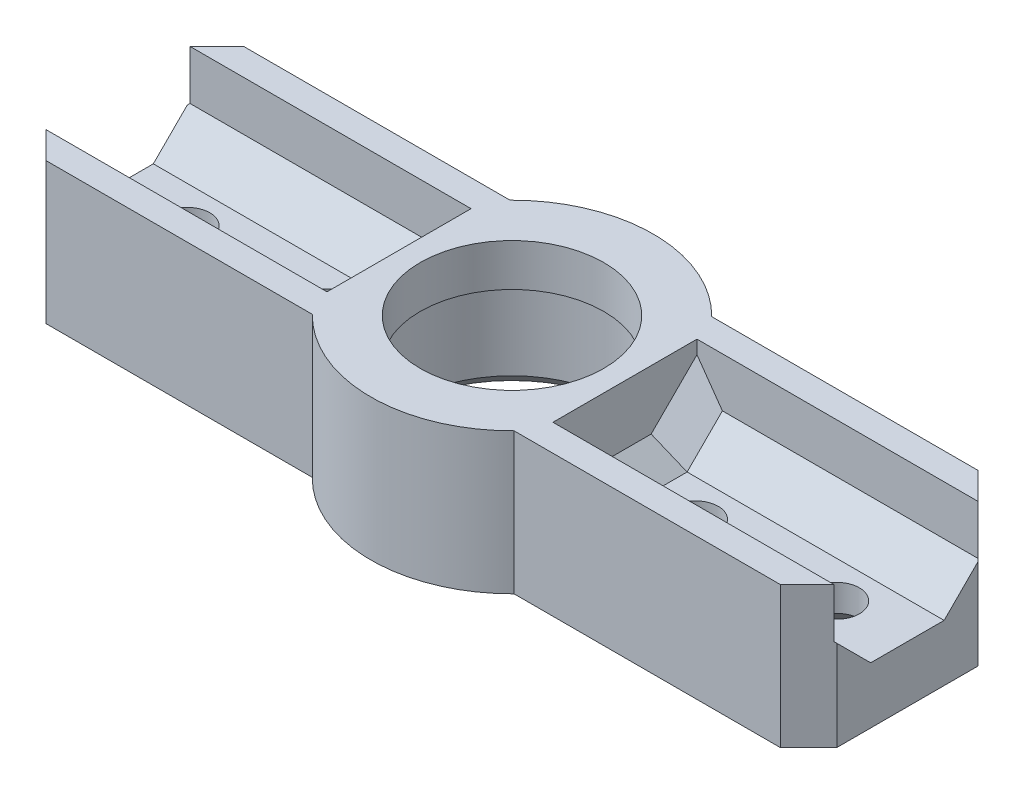
SolidWorks part; units mm, degrees
ref_plane "Plan de face" through (0, 0, 0) normal (0, 0, 1) x (1, 0, 0)
ref_plane "Plan de dessus" through (0, 0, 0) normal (0, 1, 0) x (1, 0, 0)
ref_plane "Plan de droite" through (0, 0, 0) normal (1, 0, 0) x (0, 0, -1)
sketch "Esquisse1" plane through (0, 0, 0) normal (0, 1, 0) x (1, 0, 0)
  line L0 (7.1414, 7) -> (28, 7)
  line L1 (-28, -7) -> (-7.1414, -7)
  line L2 (-28, -7) -> (-28, 7)
  line L3 (-28, 7) -> (-7.1414, 7)
  line L4 (28, -7) -> (28, 7)
  line L5 (-28, -7) -> (28, 7) construction
  line L6 (-28, 7) -> (28, -7) construction
  line L7 (7.1414, -7) -> (28, -7)
  arc A0 (-7.1414, -7) -> (7.1414, -7) centre (0, 0) ccw
  arc A1 (7.1414, 7) -> (-7.1414, 7) centre (0, 0) ccw
  dimension "D1" = 20
  dimension "D2" = 14
  dimension "D3" = 56
extrude "Boss.-Extru.1" add sketch "Esquisse1" along normal blind 10
sketch "Esquisse2" plane through (-28, 0, 0) normal (-1, 0, 0) x (0, 0, 1)
  line L0 (-7, 10) -> (7, 10) construction
  line L1 (-5.1, 10) -> (5.1, 10)
  line L2 (-5.1, 10) -> (-5.1, 4)
  line L3 (-5.1, 4) -> (5.1, 4)
  line L4 (5.1, 10) -> (5.1, 4)
  line L5 (-7, 0) -> (7, 0) construction
  point P6 (0, 0)
  dimension "D1" = 6
  dimension "D2" = 10.2
  dimension "D3" = 5.1
extrude "Enlèv. mat.-Extru.1" cut sketch "Esquisse2" against normal blind 20
chamfer "Chanfrein1" distance 2.5 angle 45 2 edges at (-18, 4, 5.1) (-18, 4, -5.1)
chamfer "Chanfrein2" distance 1.8 angle 45 3 edges at (-8, 5.25, 3.85) (-8, 4, 0) (-8, 5.25, -3.85)
mirror "Symétrie1" about plane through (0, 0, 0) normal (1, 0, 0) of "Chanfrein2", "Chanfrein1", "Enlèv. mat.-Extru.1"
sketch "Esquisse3" plane through (0, 0, 0) normal (0, -1, 0) x (1, 0, 0)
  circle A0 centre (0, 0) radius 6.5
  dimension "D1" = 13
extrude "Enlèv. mat.-Extru.2" cut sketch "Esquisse3" against normal through all
sketch "Esquisse4" plane through (0, 0, 0) normal (0, -1, 0) x (1, 0, 0)
  circle A0 centre (0, 0) radius 7.5
  dimension "D1" = 15
extrude "Enlèv. mat.-Extru.3" cut sketch "Esquisse4" against normal blind 7
chamfer "Chanfrein3" distance 1 angle 45 1 edges at (0, 0, -7.5)
sketch "Esquisse5" plane through (0, 0, 0) normal (0, -1, 0) x (1, 0, 0)
  line L0 (-32.8926, 0) -> (36.0103, 0) construction
  line L1 (28, 7) -> (28, -7) construction
  line L2 (-28, -7) -> (-28, 7) construction
  circle A0 centre (-23, 0) radius 1.6
  circle A1 centre (-13, 0) radius 1.6
  circle A2 centre (13, 0) radius 1.6
  circle A3 centre (23, 0) radius 1.6
  dimension "D1" = 3.2
  dimension "D2" = 3.2
  dimension "D3" = 3.2
  dimension "D4" = 3.2
  dimension "D5" = 5
  dimension "D6" = 10
  dimension "D7" = 10
  dimension "D8" = 5
extrude "Enlèv. mat.-Extru.4" cut sketch "Esquisse5" against normal blind 7
chamfer "Chanfrein4" distance 2.1 angle 45 4 edges at (23, 0, -1.6) (13, 0, -1.6) (-23, 0, -1.6) (-13, 0, -1.6)
chamfer "Chanfrein5" distance 2 angle 45 4 edges at (28, 5, -7) (28, 5, 7) (-28, 5, -7) (-28, 5, 7)
